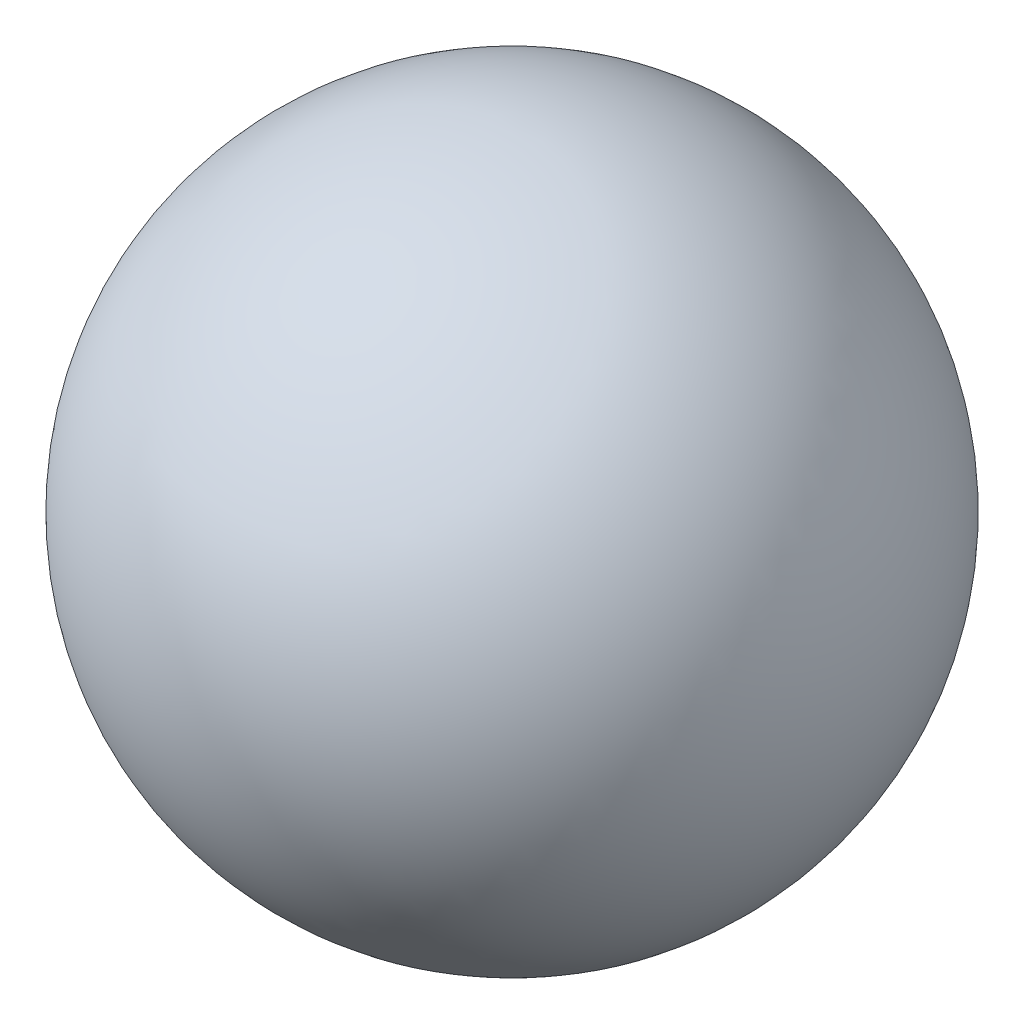
SolidWorks part; units mm, degrees
ref_plane "Front Plane" through (0, 0, 0) normal (0, 0, 1) x (1, 0, 0)
ref_plane "Top Plane" through (0, 0, 0) normal (0, 1, 0) x (1, 0, 0)
ref_plane "Right Plane" through (0, 0, 0) normal (1, 0, 0) x (0, 0, -1)
sketch "Sketch1" plane through (0, 0, 0) normal (0, 0, 1) x (1, 0, 0)
  line L0 (0, 0) -> (0, 12.5) construction
  line L1 (0, 12.5) -> (0, -12.5)
  line L2 (12.5, 0) -> (12.5, 12.5) construction
  line L3 (0, 12.5) -> (12.5, 12.5) construction
  arc A0 (0, -12.5) -> (0, 12.5) centre (0, 0) ccw
  point P3 (0, 0)
  dimension "D1" = 25
revolve "Revolve1" add sketch "Sketch1" angle 360 about L1
